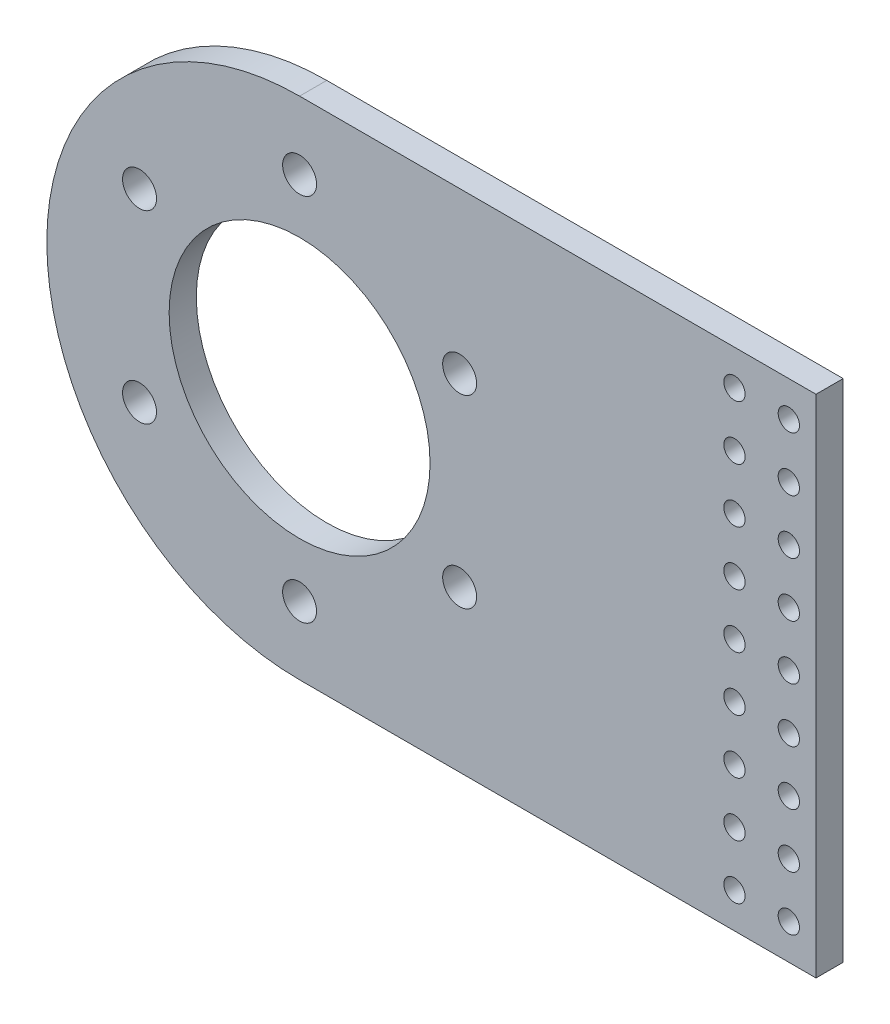
SolidWorks part; units mm, degrees
material "6061 Alloy"
ref_plane "Front Plane" through (0, 0, 0) normal (1, 0, 0) x (0, 1, 0)
ref_plane "Top Plane" through (0, 0, 0) normal (0, 0, 1) x (0, 1, 0)
ref_plane "Right Plane" through (0, 0, 0) normal (0, 1, 0) x (-1, 0, 0)
sketch "Sketch1" plane through (0, 0, 0) normal (0, 0, 1) x (0, 1, 0)
  line L0 (-59.055, 0) -> (-59.055, -120.65)
  line L1 (-59.055, -120.65) -> (59.055, -120.65)
  line L2 (59.055, -120.65) -> (59.055, 0)
  circle A0 centre (0, 0) radius 25.4 construction
  circle A1 centre (0, 0) radius 27.305 construction
  circle A2 centre (0, 0) radius 43.18 construction
  circle A3 centre (-43.18, 0) radius 15.875 construction
  circle A4 centre (-21.59, 37.395) radius 15.875 construction
  circle A5 centre (21.59, 37.395) radius 15.875 construction
  circle A6 centre (43.18, 0) radius 15.875 construction
  circle A7 centre (21.59, -37.395) radius 15.875 construction
  circle A8 centre (-21.59, -37.395) radius 15.875 construction
  arc A9 (59.055, 0) -> (-59.055, 0) centre (0, 0) ccw
  circle A10 centre (0, 0) radius 30.48
  point P5 (-43.18, 0)
  point P8 (-21.59, 37.395)
  point P13 (21.59, 37.395)
  point P16 (43.18, 0)
  point P19 (21.59, -37.395)
  point P22 (-21.59, -37.395)
  point P25 (0, 0)
  dimension "D1" = 50.8
  dimension "D2" = 1.905
  dimension "D3" = 15.875
  dimension "D4" = 31.75
  dimension "D5" = 6
  dimension "D6" = 3.175
  dimension "D7" = 120.65
extrude "Boss-Extrude1" add sketch "Sketch1" along normal blind 6.35
sketch "Sketch2" plane through (0, 0, 6.35) normal (0, 0, 1) x (1, 0, 0)
  line L0 (120.65, -59.055) -> (120.65, 59.055) construction
  point P0 (114.3, -50.8)
  point P8 (101.6, -50.8)
  point P9 (101.6, -38.1)
  point P10 (101.6, -25.4)
  point P11 (101.6, -12.7)
  point P12 (101.6, 0)
  point P13 (101.6, 12.7)
  point P14 (101.6, 25.4)
  point P15 (101.6, 38.1)
  point P16 (101.6, 50.8)
  point P17 (114.3, -38.1)
  point P18 (114.3, -25.4)
  point P19 (114.3, -12.7)
  point P20 (114.3, 0)
  point P21 (114.3, 12.7)
  point P22 (114.3, 25.4)
  point P23 (114.3, 38.1)
  point P24 (114.3, 50.8)
  dimension "D1" = 6.35
  dimension "D2" = 2
  dimension "D5" = 12.7
  dimension "D6" = 12.7
  dimension "D4" = 9
hole_wizard "#9 (0.196) Diameter Hole1" positions "Sketch2" profile "Sketch3" hole size "#9" standard "ANSI Inch" end condition through all
sketch "Sketch3" plane through (114.3, -50.8, 6.35) normal (1, 0, 0) x (0, -1, 0)
  line L0 (0, 0) -> (0, 6.35)
  line L1 (0, 6.35) -> (2.4892, 6.35)
  line L2 (2.4892, 6.35) -> (2.4892, 0)
  line L5 (2.4892, 0) -> (0, 0)
  line L11 (0, -6.35) -> (0, 107.95) construction
  dimension "Thru Hole Dia." = 4.9784
  dimension "Thru Hole Depth" = 6.35
sketch "Sketch4" plane through (0, 0, 6.35) normal (0, 0, 1) x (1, 0, 0)
  point P0 (37.395, 21.59)
  point P2 (37.395, -21.59)
  point P4 (0, -43.18)
  point P6 (-37.395, -21.59)
  point P8 (-37.395, 21.59)
  point P10 (0, 43.18)
hole_wizard "5/16 (0.3125) Diameter Hole1" positions "Sketch4" profile "Sketch5" hole size "5/16" standard "ANSI Inch" end condition through all
sketch "Sketch5" plane through (37.395, 21.59, 6.35) normal (1, 0, 0) x (0, -1, 0)
  line L0 (0, 0) -> (0, 6.35)
  line L1 (0, 6.35) -> (3.9688, 6.35)
  line L2 (3.9688, 6.35) -> (3.9688, 0)
  line L5 (3.9688, 0) -> (0, 0)
  line L11 (0, -6.35) -> (0, 107.95) construction
  dimension "Thru Hole Dia." = 7.9375
  dimension "Thru Hole Depth" = 6.35
